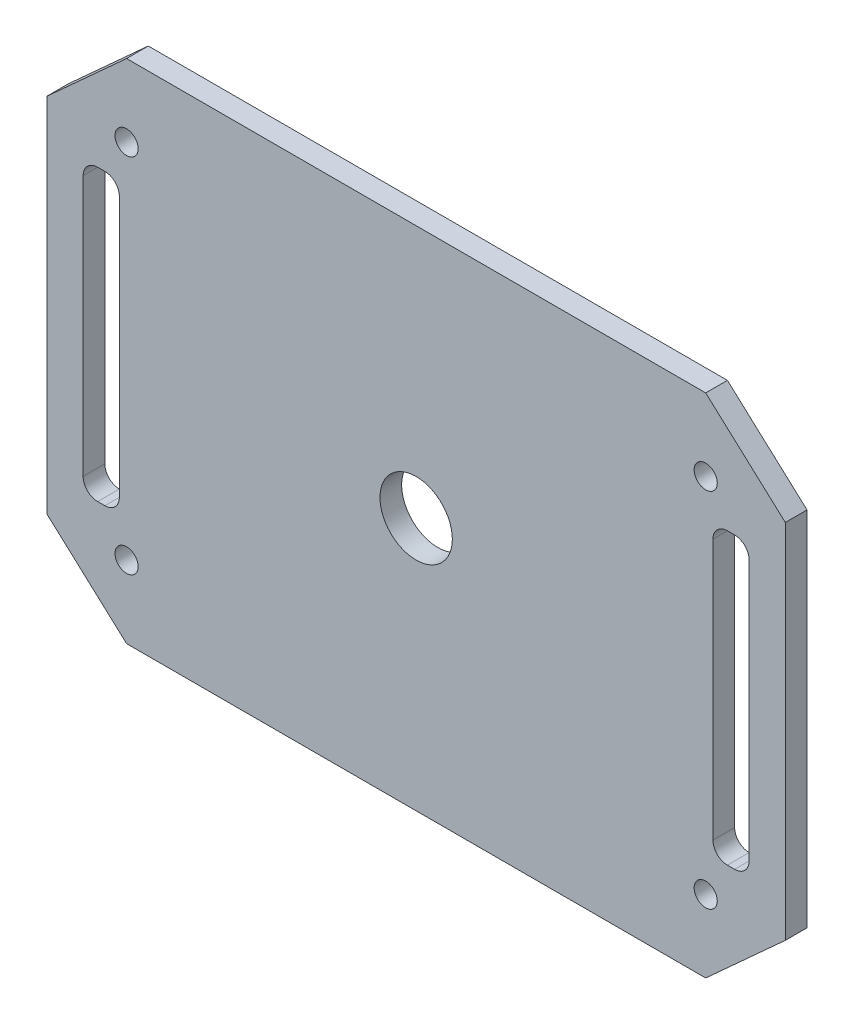
SolidWorks part; units mm, degrees
ref_plane "Front Plane" through (0, 0, 0) normal (0, 0, 1) x (1, 0, 0)
ref_plane "Top Plane" through (0, 0, 0) normal (0, 1, 0) x (1, 0, 0)
ref_plane "Right Plane" through (0, 0, 0) normal (1, 0, 0) x (0, 0, -1)
sketch "Sketch1" plane through (0, 0, 0) normal (0, 0, 1) x (1, 0, 0)
  line L0 (-10.854, -33.8449) -> (0.146, -23.8449)
  line L1 (0.146, -23.8449) -> (80.146, -23.8449)
  line L2 (80.146, -23.8449) -> (91.146, -33.8449)
  line L3 (-10.854, -83.8449) -> (0.146, -93.8449)
  line L4 (0.146, -93.8449) -> (80.146, -93.8449)
  line L5 (80.146, -93.8449) -> (91.146, -83.8449)
  line L6 (-10.854, -33.8449) -> (-10.854, -83.8449)
  line L7 (-3.854, -38.8449) -> (-2.854, -38.8449)
  line L8 (-5.854, -40.8449) -> (-5.854, -76.8449)
  line L9 (-3.854, -78.8449) -> (-2.854, -78.8449)
  line L10 (-0.854, -40.8449) -> (-0.854, -76.8449)
  line L11 (84.146, -38.8449) -> (83.146, -38.8449)
  line L12 (86.146, -40.8449) -> (86.146, -76.8449)
  line L13 (84.146, -78.8449) -> (83.146, -78.8449)
  line L14 (81.146, -40.8449) -> (81.146, -76.8449)
  line L15 (91.146, -33.8449) -> (91.146, -83.8449)
  arc A0 (86.146, -40.8449) -> (84.146, -38.8449) centre (84.146, -40.8449) ccw
  arc A1 (83.146, -38.8449) -> (81.146, -40.8449) centre (83.146, -40.8449) ccw
  arc A2 (84.146, -78.8449) -> (86.146, -76.8449) centre (84.146, -76.8449) ccw
  arc A3 (81.146, -76.8449) -> (83.146, -78.8449) centre (83.146, -76.8449) ccw
  arc A4 (-2.854, -78.8449) -> (-0.854, -76.8449) centre (-2.854, -76.8449) ccw
  arc A5 (-5.854, -76.8449) -> (-3.854, -78.8449) centre (-3.854, -76.8449) ccw
  arc A6 (-0.854, -40.8449) -> (-2.854, -38.8449) centre (-2.854, -40.8449) ccw
  arc A7 (-3.854, -38.8449) -> (-5.854, -40.8449) centre (-3.854, -40.8449) ccw
  circle A8 centre (0.146, -33.8449) radius 1.6
  circle A9 centre (80.146, -33.8449) radius 1.6
  circle A10 centre (80.146, -83.8449) radius 1.6
  circle A11 centre (0.146, -83.8449) radius 1.6
  circle A12 centre (40.146, -58.8449) radius 5
extrude "Boss-Extrude1" add sketch "Sketch1" along normal blind 3
